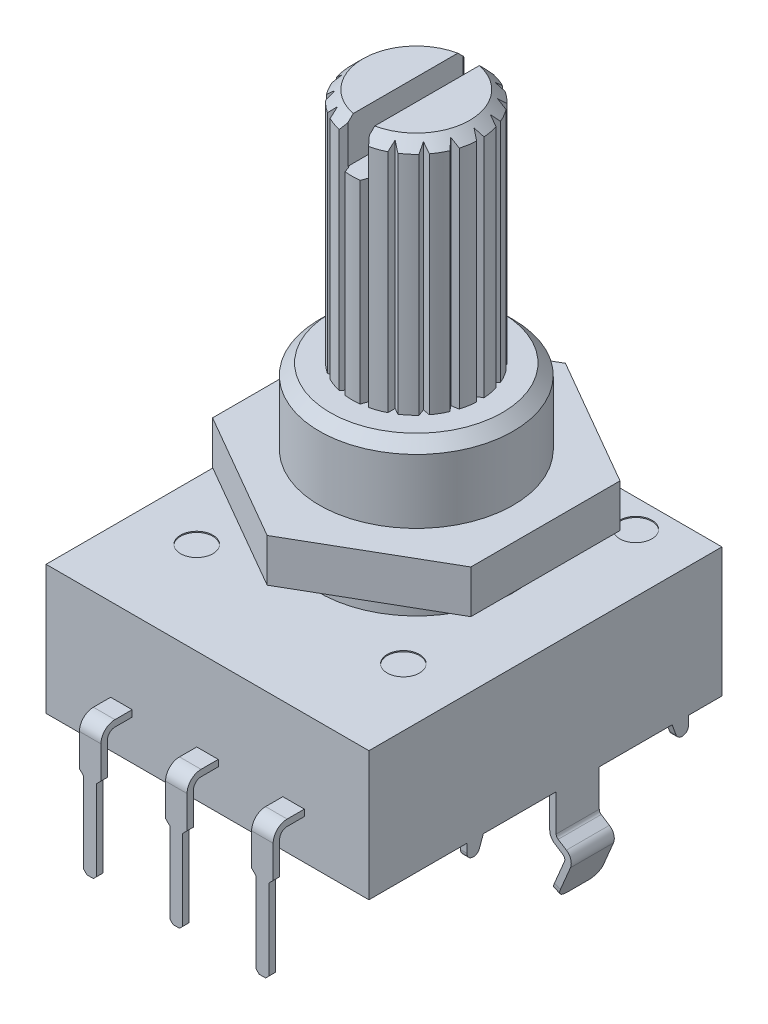
SolidWorks part; units mm, degrees
ref_plane "Front" through (0, 0, 0) normal (0, 0, 1) x (1, 0, 0)
ref_plane "Top" through (0, 0, 0) normal (0, 1, 0) x (1, 0, 0)
ref_plane "Right" through (0, 0, 0) normal (1, 0, 0) x (0, 0, -1)
sketch "Sketch1" plane through (0, 0, 0) normal (0, 1, 0) x (1, 0, 0)
  line L0 (-9.02, 0) -> (9.02, 0) construction
  line L1 (-7.5, -9.7) -> (7.5, -9.7)
  line L2 (-7.5, -9.7) -> (-7.5, 6.7)
  line L3 (-7.5, 6.7) -> (7.5, 6.7)
  line L4 (7.5, -9.7) -> (7.5, 6.7)
  line L5 (0, 0) -> (0, 6.7) construction
  dimension "D1" = 6.7
  dimension "D2" = 9.7
  dimension "D3" = 15
extrude "body" add sketch "Sketch1" against normal blind 6
sketch "Sketch2" plane through (7.5, 0, 0) normal (1, 0, 0) x (0, 0, -1)
  line L0 (0, 0) -> (0, -10.124) construction
  line L1 (0, 9.02) -> (0, -9.02) construction
  line L2 (-5.15, -6) -> (-5.15, -6.4)
  line L3 (-9.7, -6) -> (6.7, -6) construction
  line L4 (5.15, -6) -> (5.15, -6.4)
  line L5 (-4.5681, -6.5026) -> (-4.3852, -6)
  line L6 (4.5681, -6.5026) -> (4.3852, -6)
  line L7 (-5.15, -6) -> (-4.3852, -6)
  line L8 (5.15, -6) -> (4.3852, -6)
  line L9 (9.02, 0) -> (-9.02, 0) construction
  line L10 (-4.85, -6.4) -> (-4.85, -6.7) construction
  line L11 (4.85, -6.4) -> (4.85, -6.7) construction
  arc A0 (-5.15, -6.4) -> (-4.5681, -6.5026) centre (-4.85, -6.4) ccw
  arc A1 (5.15, -6.4) -> (4.5681, -6.5026) centre (4.85, -6.4) cw
  dimension "D3" = 0.3
  dimension "D1" = 10.3
  dimension "D2" = 6.7
  dimension "D4" = 20
extrude "pcb spacers" add sketch "Sketch2" against normal blind 0.3
ref_plane "PCB Surface" through (0, -6.7, 0) normal (0, 1, 0) x (-1, 0, 0)
sketch "PCB sketch" plane through (0, -6.7, 0) normal (0, 1, 0) x (-1, 0, 0)
  line L0 (0, 0) -> (0, 11) construction
  line L1 (-7.5, 1.05) -> (-7.5, -1.05)
  line L2 (7.5, 1.05) -> (5.9, 1.05)
  line L3 (7.5, 1.05) -> (7.5, -1.05)
  line L4 (7.5, -1.05) -> (5.9, -1.05)
  line L5 (5.9, 1.05) -> (5.9, -1.05)
  line L6 (-7.5, 1.05) -> (-5.9, 1.05)
  line L7 (-5.9, 1.05) -> (-5.9, -1.05)
  line L8 (-7.5, -1.05) -> (-5.9, -1.05)
  line L9 (0, 0) -> (7.5, 0) construction
  line L10 (0, 0) -> (-7.5, 0) construction
  line L11 (6.7, 1.05) -> (6.7, -1.05) construction
  line L12 (-6.7, 1.05) -> (-6.7, -1.05) construction
  circle A0 centre (0, 0) radius 1.5
  circle A1 centre (4, 11) radius 0.5
  circle A2 centre (0, 11) radius 0.5
  circle A3 centre (-4, 11) radius 0.5
  dimension "D1" = 1
  dimension "D4" = 3
  dimension "D2" = 2.1
  dimension "D3" = 1.6
  dimension "D5" = 13.4
  dimension "D6" = 11
  dimension "D7" = 8
sketch "Sketch3" plane through (0, 0, 0) normal (0, 0, 1) x (1, 0, 0)
  line L0 (7.5, -6) -> (7.5, -7.7032)
  line L1 (7.5916, -7.8712) -> (7.9711, -8.1161)
  line L2 (8.1608, -8.7302) -> (7.5, -10.3)
  line L4 (7.2, -6.7) -> (7.5, -6.7) construction
  line L5 (7.2, -6) -> (7.2, -7.7032)
  line L6 (7.4289, -8.1233) -> (7.8084, -8.3682)
  line L7 (7.8843, -8.6138) -> (7.2235, -10.1836)
  line L8 (7.2235, -10.1836) -> (7.5, -10.3)
  line L9 (7.2, -6) -> (7.5, -6)
  arc A0 (7.5, -7.7032) -> (7.5916, -7.8712) centre (7.7, -7.7032) ccw
  arc A1 (8.1608, -8.7302) -> (7.9711, -8.1161) centre (7.7, -8.5362) ccw
  arc A2 (7.2, -7.7032) -> (7.4289, -8.1233) centre (7.7, -7.7032) ccw
  arc A3 (7.8843, -8.6138) -> (7.8084, -8.3682) centre (7.7, -8.5362) ccw
  dimension "D2" = 0.2
  dimension "D3" = 0.5
  dimension "D1" = 3.6
  dimension "D4" = 100
  dimension "D5" = 0.7
  dimension "D6" = 0.3
extrude "right pcb tang" add sketch "Sketch3" along normal mid plane 2
fillet "Fillet1" radius 0.5 2 edges at (7.3618, -10.2418, -1) (7.3618, -10.2418, 1)
mirror "left pcb tang" about plane through (0, 0, 0) normal (1, 0, 0) of "Fillet1", "right pcb tang", "pcb spacers"
sketch "Sketch4" plane through (0, 0, 0) normal (0, 1, 0) x (1, 0, 0)
  line L0 (0, 0) -> (0, 5.5558) construction
  line L1 (0, -9.8175) -> (0, 9.8175) construction
  line L2 (0, 0) -> (5.8963, 0) construction
  line L3 (-9.02, 0) -> (9.02, 0) construction
  circle A0 centre (-4.8, 5.4) radius 0.75
  circle A1 centre (4.8, 5.4) radius 0.75
  circle A2 centre (4.8, -5.4) radius 0.75
  circle A3 centre (-4.8, -5.4) radius 0.75
  dimension "D2" = 10.8
  dimension "D3" = 1.5
  dimension "D1" = 9.6
extrude "dimples" cut sketch "Sketch4" against normal blind 0.05
sketch "Sketch5" plane through (0, 0, 0) normal (1, 0, 0) x (0, 0, -1)
  line L0 (-9.7, -4) -> (-10.5, -4)
  line L1 (-9.7, -6) -> (-9.7, 0) construction
  line L2 (-11, -4.5) -> (-11, -10.0954)
  line L3 (0, 9.02) -> (0, -9.02) construction
  line L4 (-9.7, -6) -> (-5.15, -6) construction
  arc A1 (-5.15, -6.4) -> (-4.5681, -6.5026) centre (-4.85, -6.4) ccw construction
  arc A2 (-11, -4.5) -> (-10.5, -4) centre (-10.5, -4.5) cw
  point P8 (-4.9021, -6.6954)
  dimension "D1" = 3.4
  dimension "D4" = 0.5
  dimension "D2" = 11
  dimension "D3" = 2
extrude "contacts" add sketch "Sketch5" along normal mid plane 9 thin thin type mid plane wall 0.3
sketch "Sketch6" plane through (0, 0, 11.15) normal (0, 0, 1) x (1, 0, 0)
  line L0 (0, 0) -> (0, -10.9402) construction
  line L1 (0, -9.8175) -> (0, 9.8175) construction
  line L2 (-4.5, -6) -> (-4.3, -6.2)
  line L3 (-4.5, -6) -> (-4.5, -10.0954)
  line L4 (-4.5, -10.0954) -> (-4.3, -10.0954)
  line L5 (-4.5, -4.5) -> (-4.5, -10.0954) construction
  line L6 (-7.5, -6) -> (7.5, -6) construction
  line L7 (4.5, -6) -> (4.3, -6.2)
  line L8 (-4.3, -6.2) -> (-4.3, -10.0954)
  line L9 (4.5, -10.0954) -> (-4.5, -10.0954) construction
  line L10 (4.3, -6.2) -> (4.3, -10.0954)
  line L11 (-3.7, -10.0954) -> (-3.7, -6.2)
  line L12 (3.7, -10.0954) -> (3.7, -6.2)
  line L13 (-3.7, -6.2) -> (-3.5, -6)
  line L14 (3.7, -6.2) -> (3.5, -6)
  line L15 (-0.5, -6) -> (-0.3, -6.2)
  line L16 (0.5, -6) -> (0.3, -6.2)
  line L17 (-0.3, -6.2) -> (-0.3, -10.0954)
  line L18 (0.3, -6.2) -> (0.3, -10.0954)
  line L19 (-3.7, -10.0954) -> (-0.3, -10.0954)
  line L20 (0.3, -10.0954) -> (3.7, -10.0954)
  line L21 (4.5, -6) -> (4.5, -10.0954)
  line L22 (-3.5, -6) -> (-3.5, -3.85)
  line L23 (4.5, -3.85) -> (-4.5, -3.85) construction
  line L24 (-4, -10.0954) -> (-4, -6.5934) construction
  line L25 (4, -10.0954) -> (4, -6.5934) construction
  line L26 (3.5, -6) -> (3.5, -3.85)
  line L27 (-0.5, -6) -> (-0.5, -3.85)
  line L28 (0.5, -6) -> (0.5, -3.85)
  line L29 (-3.5, -3.85) -> (-0.5, -3.85)
  line L30 (3.5, -3.85) -> (0.5, -3.85)
  line L31 (4.3, -10.0954) -> (4.5, -10.0954)
  dimension "D1" = 0.6
  dimension "D2" = 8
  dimension "D3" = 1
  dimension "D4" = 0.6
extrude "Cut-Extrude2" cut sketch "Sketch6" against normal up to surface (1.45 mm away)
chamfer "Chamfer1" distance 0.15 angle 45 6 edges at (4.3, -10.0954, 11) (3.7, -10.0954, 11) (0.3, -10.0954, 11) (-0.3, -10.0954, 11) (-3.7, -10.0954, 11) (-4.3, -10.0954, 11)
sketch "Sketch7" plane through (0, 0, 0) normal (0, 0, 1) x (1, 0, 0)
  line L0 (0, 0) -> (0, 18.6617) construction
  line L1 (-4.5, 0) -> (-4.5, 6.5)
  line L2 (-7.5, 0) -> (7.5, 0) construction
  line L3 (-4, 7) -> (-2.98, 7)
  line L4 (-2.98, 7) -> (-2.98, 17.5)
  line L5 (-2.98, 17.5) -> (-2.48, 18)
  line L6 (-2.48, 18) -> (0, 18)
  line L7 (0, 18) -> (0, 0)
  line L8 (0, 0) -> (-4.5, 0)
  line L9 (-4, 7) -> (-4.5, 6.5)
  dimension "D1" = 7
  dimension "D2" = 18
  dimension "D3" = 5.96
  dimension "D4" = 9
  dimension "D5" = 45
  dimension "D6" = 0.5
revolve "main stem" add sketch "Sketch7" angle 360 about L0
cosmetic thread "Cosmetic Thread1" parameters "D2"=8
sketch "Sketch8" plane through (0, 0, 0) normal (0, 0, 1) x (1, 0, 0)
  line L0 (0, 0) -> (0, 18) construction
  line L1 (2.48, 18) -> (-2.48, 18) construction
  line L2 (-0.5, 16) -> (-0.5, 18)
  line L3 (-0.5, 16) -> (0.5, 16)
  line L4 (-0.5, 18) -> (0.5, 18)
  line L5 (0.5, 16) -> (0.5, 18)
  line L6 (-0.5, 16) -> (0.5, 18) construction
  line L7 (-0.5, 18) -> (0.5, 16) construction
  point P6 (0, 17)
  dimension "D1" = 1
  dimension "D2" = 2
extrude "screwdriver slot" cut sketch "Sketch8" against normal up to next and the other way up to next
sketch "Sketch9" plane through (0, 7, 0) normal (0, 1, 0) x (1, 0, 0)
  line L0 (2.68, 0) -> (2.9751, 0.1704)
  line L1 (2.68, 0) -> (2.9751, -0.1704)
  line L2 (2.68, 0) -> (3.094, 0) construction
  line L3 (-9.02, 0) -> (9.02, 0) construction
  arc A1 (0.5, -2.9378) -> (0.5, 2.9378) centre (0, 0) ccw construction
  circle A2 centre (0, 0) radius 2.98 construction
  arc A3 (2.9751, -0.1704) -> (2.9751, 0.1704) centre (0, 0) ccw
  dimension "D2" = 0.3
  dimension "D1" = 60
extrude "seration" cut sketch "Sketch9" along normal up to next
pattern_circular "18 cerations" count 18 over 360 about axis through (0, 0, 0) along (0, 1, 0) of "seration"
ref_plane "Nut Surface, adjust as needed" through (0, 1.524, 0) normal (0, 1, 0) x (-1, 0, 0)
sketch "Sketch10" plane through (0, 1.524, 0) normal (0, 1, 0) x (-1, 0, 0)
  line L1 (0, 6.9282) -> (-6, 3.4641)
  line L2 (-6, 3.4641) -> (-6, -3.4641)
  line L3 (-6, -3.4641) -> (0, -6.9282)
  line L4 (0, -6.9282) -> (6, -3.4641)
  line L5 (6, -3.4641) -> (6, 3.4641)
  line L6 (6, 3.4641) -> (0, 6.9282)
  circle A0 centre (0, 0) radius 6 construction
  circle A1 centre (0, 0) radius 4
  dimension "D2" = 8
  dimension "D1" = 12
extrude "nut" add sketch "Sketch10" along normal blind 2 separate body
